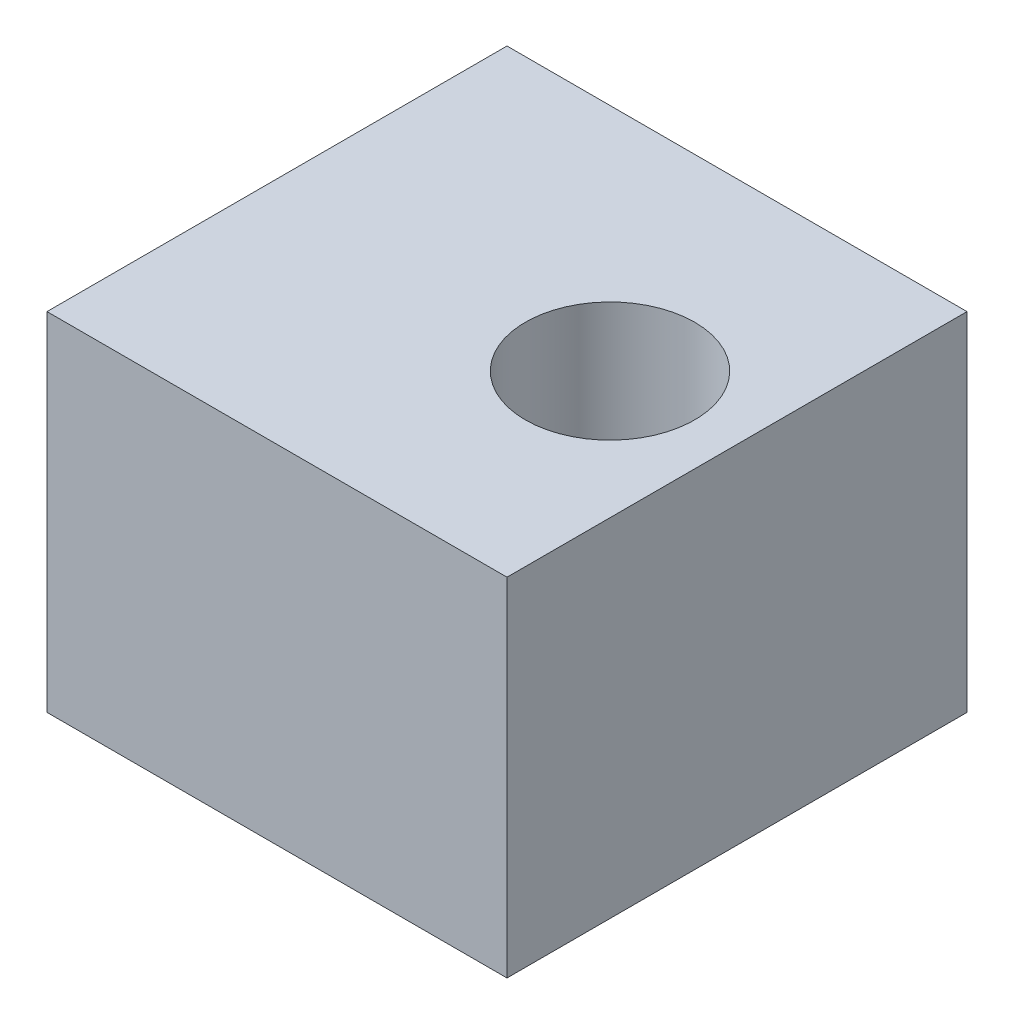
SolidWorks part; units mm, degrees
ref_plane "Front Plane" through (0, 0, 0) normal (0, 0, 1) x (1, 0, 0)
ref_plane "Top Plane" through (0, 0, 0) normal (0, 1, 0) x (1, 0, 0)
ref_plane "Right Plane" through (0, 0, 0) normal (1, 0, 0) x (0, 0, -1)
sketch "Sketch1" plane through (0, 0, 0) normal (0, 1, 0) x (1, 0, 0)
  line L1 (-8.15, -8.15) -> (8.15, -8.15)
  line L2 (-8.15, -8.15) -> (-8.15, 8.15)
  line L3 (-8.15, 8.15) -> (8.15, 8.15)
  line L4 (8.15, -8.15) -> (8.15, 8.15)
  line L5 (-8.15, -8.15) -> (8.15, 8.15) construction
  line L6 (-8.15, 8.15) -> (8.15, -8.15) construction
  point P0 (0, 0)
  dimension "D2" = 16.3
extrude "Boss-Extrude1" add sketch "Sketch1" along normal blind 12.3
sketch "Sketch2" plane through (0, 0, 0) normal (0, 1, 0) x (1, 0, 0)
  line L0 (8.15, -8.15) -> (8.15, 8.15) construction
  line L1 (0, 0) -> (3.65, 0) construction
  circle A0 centre (3.65, 0) radius 3
  dimension "D1" = 6
  dimension "D2" = 4.5
extrude "Cut-Extrude1" cut sketch "Sketch2" along normal up to surface (12.3 mm away) up to face at (0, 12.3, 0)
